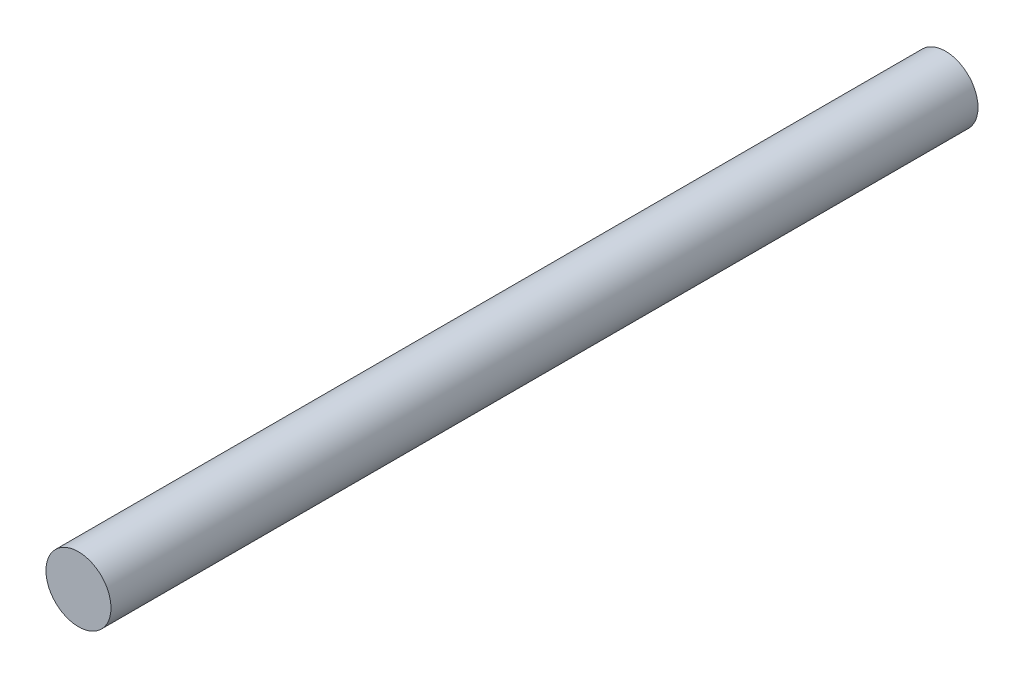
SolidWorks part; units mm, degrees
ref_plane "Front Plane" through (0, 0, 0) normal (0, 0, 1) x (1, 0, 0)
ref_plane "Top Plane" through (0, 0, 0) normal (0, 1, 0) x (1, 0, 0)
ref_plane "Right Plane" through (0, 0, 0) normal (1, 0, 0) x (0, 0, -1)
sketch "Sketch1" plane through (0, 0, 0) normal (0, 0, 1) x (1, 0, 0)
  circle A0 centre (0, 0) radius 9.525
  dimension "D1" = 19.05
extrude "Boss-Extrude2" add sketch "Sketch1" along normal mid plane 254
